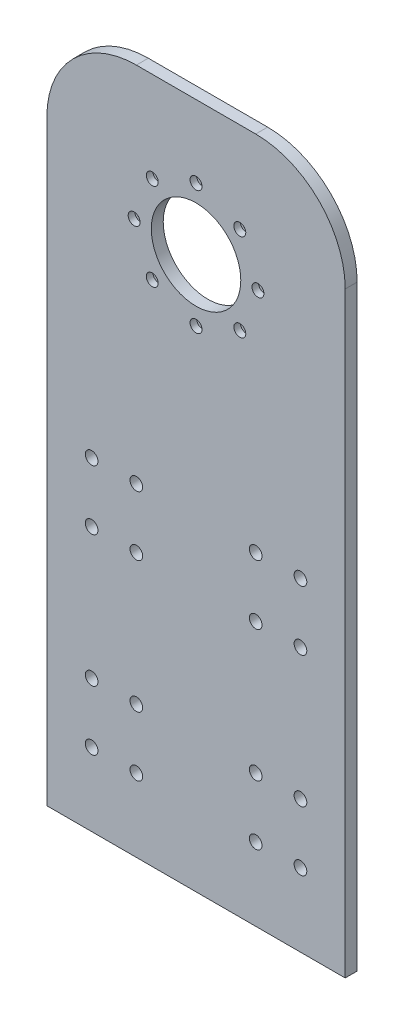
SolidWorks part; units mm, degrees
ref_plane "前视基准面" through (0, 0, 0) normal (0, 0, 1) x (1, 0, 0)
ref_plane "上视基准面" through (0, 0, 0) normal (0, 1, 0) x (1, 0, 0)
ref_plane "右视基准面" through (0, 0, 0) normal (1, 0, 0) x (0, 0, -1)
other "Configuration Table"
sketch "草图1" plane through (0, 0, 0) normal (0, 0, 1) x (1, 0, 0)
  line L0 (0, 0) -> (0, 498.031) construction
  line L1 (100, 0) -> (-100, 0)
  line L2 (-100, 0) -> (-100, 460)
  line L3 (-100, 460) -> (100, 460)
  line L4 (100, 0) -> (100, 460)
  point P7 (0, 460)
  dimension "D1" = 460
  dimension "D2" = 100
extrude "凸台-拉伸1" add sketch "草图1" along normal blind 8
sketch "草图2" plane through (0, 0, 0) normal (0, 0, -1) x (-1, 0, 0)
  line L0 (100, 0) -> (-100, 0) construction
  circle A0 centre (0, 370) radius 30
  circle A1 centre (0, 370) radius 81.25 construction
  dimension "D1" = 60
  dimension "D3" = 162.5
  dimension "D2" = 370
extrude "切除-拉伸1" cut sketch "草图2" against normal blind 10
sketch "草图3" plane through (0, 0, 0) normal (0, 0, -1) x (-1, 0, 0)
  line L0 (0, 370) -> (0, 473.0171) construction
  circle A0 centre (0, 370) radius 41.5 construction
  circle A1 centre (0, 411.5) radius 2.25
  circle A2 centre (29.3449, 399.3449) radius 2.25
  circle A3 centre (41.5, 370) radius 2.25
  circle A4 centre (29.3449, 340.6551) radius 2.25
  circle A5 centre (0, 328.5) radius 2.25
  circle A6 centre (-29.3449, 340.6551) radius 2.25
  circle A7 centre (-41.5, 370) radius 2.25
  circle A8 centre (-29.3449, 399.3449) radius 2.25
  point P23 (0, 370)
  dimension "D1" = 83
  dimension "D2" = 4.5
  dimension "D3" = 8
extrude "切除-拉伸2" cut sketch "草图3" against normal blind 10
sketch "草图4" plane through (0, 0, 8) normal (0, 0, 1) x (1, 0, 0)
  circle A0 centre (29.3449, 399.3449) radius 4
  circle A1 centre (41.5, 370) radius 4
  circle A2 centre (29.3449, 340.6551) radius 4
  circle A3 centre (0, 328.5) radius 4
  circle A4 centre (-29.3449, 340.6551) radius 4
  circle A5 centre (-41.5, 370) radius 4
  circle A6 centre (-29.3449, 399.3449) radius 4
  circle A7 centre (0, 411.5) radius 4
  point P19 (0, 370)
  dimension "D1" = 8
  dimension "D2" = 8
extrude "切除-拉伸3" cut sketch "草图4" against normal blind 4.4
fillet "圆角1" radius 60 2 edges at (-100, 460, 4) (100, 460, 4)
sketch "草图5" plane through (0, 0, 0) normal (0, 0, -1) x (-1, 0, 0)
  line L0 (0, 0) -> (0, 210.4688) construction
  line L1 (23.8213, 108) -> (84.3504, 108) construction
  line L2 (23.8213, 236) -> (84.3504, 236) construction
  line L3 (78.9299, 30) -> (16.8198, 30) construction
  line L4 (100, 0) -> (-100, 0) construction
  line L5 (78.9299, 158) -> (16.8198, 158) construction
  line L6 (-78.9299, 158) -> (-16.8198, 158) construction
  line L7 (-78.9299, 30) -> (-16.8198, 30) construction
  line L8 (-23.8213, 236) -> (-84.3504, 236) construction
  line L9 (-23.8213, 108) -> (-84.3504, 108) construction
  circle A0 centre (40, 49) radius 4.25
  circle A1 centre (70, 49) radius 4.25
  circle A2 centre (40, 89) radius 4.25
  circle A3 centre (70, 89) radius 4.25
  circle A4 centre (40, 217) radius 4.25
  circle A5 centre (40, 177) radius 4.25
  circle A6 centre (70, 177) radius 4.25
  circle A7 centre (70, 217) radius 4.25
  circle A8 centre (-70, 217) radius 4.25
  circle A9 centre (-70, 177) radius 4.25
  circle A10 centre (-40, 177) radius 4.25
  circle A11 centre (-40, 217) radius 4.25
  circle A12 centre (-70, 89) radius 4.25
  circle A13 centre (-40, 89) radius 4.25
  circle A14 centre (-70, 49) radius 4.25
  circle A15 centre (-40, 49) radius 4.25
  dimension "D1" = 8.5
  dimension "D2" = 30
  dimension "D3" = 30
  dimension "D4" = 40
  dimension "D5" = 19
  dimension "D6" = 40
  dimension "D7" = 19
  dimension "D8" = 2
extrude "切除-拉伸4" cut sketch "草图5" against normal blind 10
